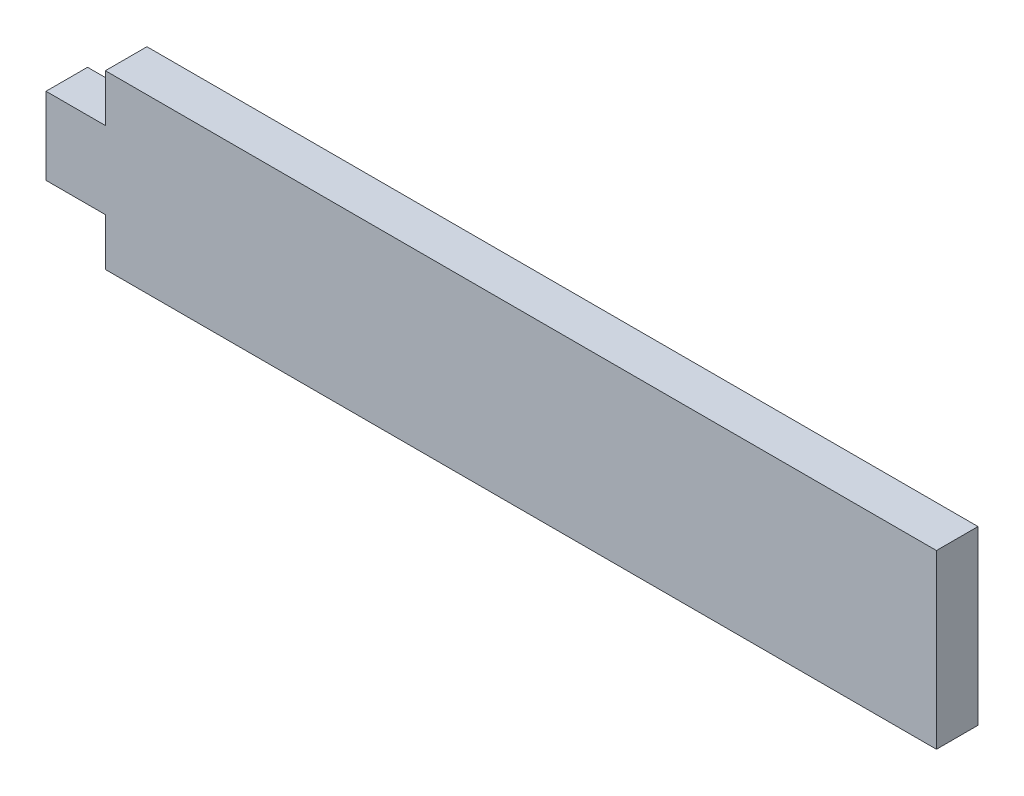
SolidWorks part; units mm, degrees
material "Pino"
ref_plane "Alzado" through (0, 0, 0) normal (0, 0, 1) x (1, 0, 0)
ref_plane "Planta" through (0, 0, 0) normal (0, 1, 0) x (1, 0, 0)
ref_plane "Vista lateral" through (0, 0, 0) normal (1, 0, 0) x (0, 0, -1)
sketch "Croquis1" plane through (0, 0, 0) normal (0, 0, 1) x (1, 0, 0)
  line L1 (-650, -72.5) -> (650, -72.5)
  line L2 (-650, -72.5) -> (-650, 72.5)
  line L3 (-650, 72.5) -> (650, 72.5)
  line L4 (650, -72.5) -> (650, 72.5)
  line L5 (-650, -72.5) -> (650, 72.5) construction
  line L6 (-650, 72.5) -> (650, -72.5) construction
  point P0 (0, 0)
  dimension "D1" = 1300
  dimension "D2" = 145
extrude "Saliente-Extruir1" add sketch "Croquis1" along normal blind 35
sketch "Croquis2" plane through (-650, 0, 0) normal (-1, 0, 0) x (0, 0, 1)
  line L0 (35, 72.5) -> (35, -72.5) construction
  line L1 (0, 72.5) -> (35, 72.5)
  line L2 (0, 72.5) -> (0, -72.5)
  line L3 (0, -72.5) -> (35, -72.5)
  line L4 (35, 72.5) -> (35, -72.5)
  dimension "D1" = 145
extrude "Cortar-Extruir1" cut sketch "Croquis2" against normal blind 600
sketch "Croquis3" plane through (-50, 0, 0) normal (-1, 0, 0) x (0, 0, 1)
  line L0 (0, 72.5) -> (0, -72.5) construction
  line L1 (0, 32.5) -> (35, 32.5)
  line L2 (0, 32.5) -> (0, -32.5)
  line L3 (0, -32.5) -> (35, -32.5)
  line L4 (35, 32.5) -> (35, -32.5)
  line L5 (0, 32.5) -> (35, 32.5) construction
  line L6 (35, -72.5) -> (35, 72.5) construction
  line L7 (35, -32.5) -> (0, -32.5) construction
extrude "Saliente-Extruir2" add sketch "Croquis3" along normal blind 50
